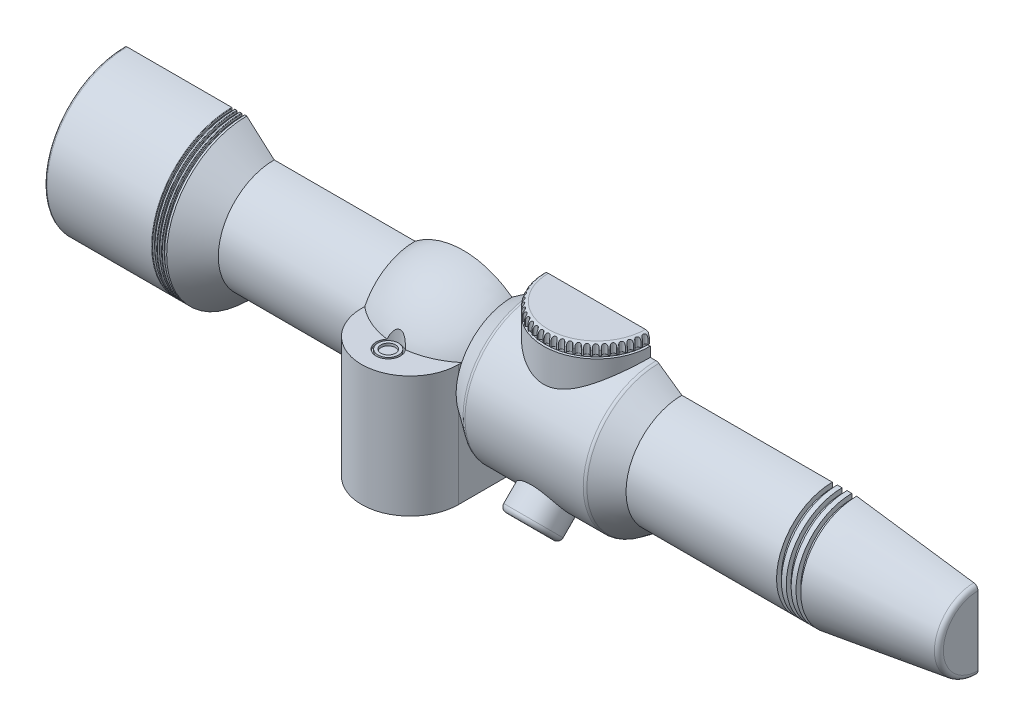
SolidWorks part; units mm, degrees
ref_plane "Front Plane" through (0, 0, 0) normal (0, 0, 1) x (1, 0, 0)
ref_plane "Top Plane" through (0, 0, 0) normal (0, 1, 0) x (1, 0, 0)
ref_plane "Right Plane" through (0, 0, 0) normal (1, 0, 0) x (0, 0, -1)
sketch "Sketch1" plane through (0, 0, 0) normal (1, 0, 0) x (0, 0, -1)
  circle A0 centre (0, 0) radius 16.5
  dimension "D1" = 33
extrude "Boss-Extrude1" add sketch "Sketch1" along normal blind 25.15
sketch "Sketch2" plane through (0, 0, 0) normal (-1, 0, 0) x (0, 0, 1)
  circle A0 centre (0, 0) radius 14.125
  dimension "D1" = 28.25
extrude "Cut-Extrude1" cut sketch "Sketch2" against normal blind 1
sketch "Sketch3" plane through (1, 0, 0) normal (-1, 0, 0) x (0, 0, 1)
  circle A0 centre (0, 0) radius 13.125
  dimension "D1" = 26.25
ref_plane "Plane1" through (25.15, 0, 0) normal (0, -1, 0) x (0, 0, 1)
extrude "Cut-Extrude6" cut sketch "Sketch3" against normal blind 1 contours A0
sketch "Sketch14" plane through (2, 0, 0) normal (-1, 0, 0) x (0, 0, 1)
  circle A0 centre (0, 0) radius 12.125
  dimension "D1" = 24.25
extrude "Cut-Extrude7" cut sketch "Sketch14" against normal blind 1
sketch "Sketch15" plane through (3, 0, 0) normal (-1, 0, 0) x (0, 0, 1)
  circle A0 centre (0, 0) radius 11.125
  dimension "D1" = 22.25
extrude "Cut-Extrude8" cut sketch "Sketch15" against normal blind 1
sketch "Sketch16" plane through (4, 0, 0) normal (-1, 0, 0) x (0, 0, 1)
  circle A0 centre (0, 0) radius 10.125
  dimension "D1" = 20.25
extrude "Cut-Extrude9" cut sketch "Sketch16" against normal blind 1
sketch "Sketch17" plane through (5, 0, 0) normal (-1, 0, 0) x (0, 0, 1)
  circle A0 centre (0, 0) radius 9.125
  dimension "D1" = 18.25
extrude "Cut-Extrude10" cut sketch "Sketch17" against normal blind 3
sketch "Sketch18" plane through (0, 0, 0) normal (0, 1, 0) x (1, 0, 0)
  line L0 (25.15, 0) -> (0, 0) construction
  line L1 (6.4671, 0) -> (8, 0)
  line L2 (8, 9.125) -> (8, -9.125) construction
  line L3 (8, 0) -> (8, 9.125)
  spline S0 degree 2 poles (8, 9.125) (6.4671, 4.5625) (6.4671, 0) knots 0 0 0 0.5 0.5 0.5
revolve "Revolve1" add sketch "Sketch18" angle 360 about axis through (25.15, 0, 0) along (-1, 0, 0)
sketch "Sketch20" plane through (0, 0, 0) normal (0, 1, 0) x (1, 0, 0)
  line L0 (25.15, 0) -> (30.8, 0)
  line L1 (25.15, -16.5) -> (25.15, 16.5) construction
  line L2 (25.15, 0) -> (0, 0) construction
  line L3 (30.8, 0) -> (30.8, 11.5)
  line L4 (30.8, 11.5) -> (25.15, 16.5)
  line L5 (25.15, 16.5) -> (25.15, 0)
  line L6 (25.15, 0) -> (25.0816, -0.0545)
  dimension "D1" = 11.5
  dimension "D2" = 5.65
revolve "Revolve5" add sketch "Sketch20" angle 360 about L0
sketch "Sketch21" plane through (30.8, 0, 0) normal (1, 0, 0) x (0, 0, -1)
  circle A0 centre (0, 0) radius 11.5
extrude "Shaft" add sketch "Sketch21" along normal blind 120
sketch "Sketch25" plane through (0, 0, 0) normal (0, 1, 0) x (1, 0, 0)
  line L0 (23.15, 16.5) -> (23.65, 16.5)
  line L1 (25.15, 16.5) -> (0, 16.5) construction
  line L2 (24.65, 16.5) -> (24.65, 16)
  line L3 (24.65, 16) -> (24.15, 16)
  line L4 (24.15, 16) -> (24.15, 16.5)
  line L5 (25.15, 16.5) -> (0, 16.5) construction
  line L7 (25.15, 16.5) -> (0, 16.5) construction
  line L8 (23.65, 16.5) -> (23.65, 16)
  line L9 (23.65, 16) -> (23.15, 16)
  line L10 (23.15, 16) -> (23.15, 16.5)
  line L11 (25.15, 16.5) -> (0, 16.5) construction
  line L12 (24.15, 16.5) -> (24.65, 16.5)
  line L13 (25.15, 16.5) -> (0, 16.5) construction
  line L14 (22.65, 16.5) -> (22.65, 16)
  line L15 (22.65, 16) -> (22.15, 16)
  line L16 (22.15, 16) -> (22.15, 16.5)
  line L17 (25.15, 16.5) -> (0, 16.5) construction
  line L18 (22.15, 16.5) -> (22.65, 16.5)
  line L20 (23.65, 16.5) -> (23.6371, 16.4877)
  dimension "D1" = 0.5
  dimension "D2" = 0.5
  dimension "D3" = 0.5
  dimension "D4" = 0.5
  dimension "D5" = 0.5
  dimension "D6" = 0.5
  dimension "D8" = 0.5
  dimension "D9" = 0.5
revolve "Cut-Revolve13" cut sketch "Sketch25" angle 360 about axis through (25.15, 0, 0) along (-1, 0, 0)
fillet "Fillet1" radius 0.1 6 edges at (24.65, 0, -16.5) (24.15, 0, -16.5) (23.65, 0, -16.5) (23.15, 0, -16.5) (22.65, 0, -16.5) (22.15, 0, -16.5)
fillet "Fillet2" radius 0.5 1 edges at (0, 0, -16.5)
sketch "Sketch26" plane through (0, 0, 0) normal (0, 1, 0) x (1, 0, 0)
  line L0 (150.8, -11.5) -> (150.8, 0)
  line L1 (150.8, -11.5) -> (150.8, 11.5) construction
  line L2 (150.8, 0) -> (175.8, 0)
  line L3 (150.8, 0) -> (30.8, 0) construction
  line L4 (175.8, 0) -> (175.8, -7.1302)
  line L5 (174.9386, -8.1206) -> (150.8, -11.5)
  arc A0 (175.8, -7.1302) -> (174.9386, -8.1206) centre (174.8, -7.1302) cw
  point P12 (175.8, -8)
  dimension "D3" = 1
  dimension "D1" = 25
  dimension "D2" = 8
revolve "Revolve6" add sketch "Sketch26" angle 360 about axis through (150.8, 0, 0) along (-1, 0, 0)
sketch "Sketch27" plane through (0, 0, 0) normal (0, 1, 0) x (1, 0, 0)
  line L0 (147.8, -11.5) -> (147.8, -10.5)
  line L1 (150.8, -11.5) -> (149.8, -11.5)
  line L2 (150.8, -11.5) -> (150.8, -10.5)
  line L3 (150.8, -10.5) -> (149.8, -10.5)
  line L4 (149.8, -11.5) -> (149.8, -10.5)
  line L5 (148.8, -11.5) -> (147.8, -11.5)
  line L6 (148.8, -11.5) -> (148.8, -10.5)
  line L7 (148.8, -10.5) -> (147.8, -10.5)
  line L8 (145.8, -11.5) -> (145.8, -10.5)
  line L9 (146.8, -11.5) -> (145.8, -11.5)
  line L10 (146.8, -11.5) -> (146.8, -10.5)
  line L11 (146.8, -10.5) -> (145.8, -10.5)
  dimension "D1" = 1
  dimension "D2" = 1
  dimension "D3" = 3
revolve "Cut-Revolve14" cut sketch "Sketch27" angle 360 about axis through (150.8, 0, 0) along (-1, 0, 0)
sketch "Sketch28" plane through (0, 0, 0) normal (0, 1, 0) x (1, 0, 0)
  line L0 (145.8, 0) -> (30.8, 0) construction
  line L1 (59.8, 11) -> (59.8, -11)
  line L2 (79.8, -11) -> (79.8, 11)
  line L3 (30.8, 11.5) -> (30.8, -11.5) construction
  arc A0 (79.8, 11) -> (59.8, 11) centre (69.8, 11) ccw
  arc A1 (59.8, -11) -> (79.8, -11) centre (69.8, -11) ccw
  dimension "D1" = 20
  dimension "D2" = 20
  dimension "D3" = 22
  dimension "D4" = 11
  dimension "D5" = 29
extrude "Boss-Extrude2" add sketch "Sketch28" against normal blind 20 and the other way blind 5
sketch "Sketch29" plane through (0, -20, 0) normal (0, -1, 0) x (1, 0, 0)
  circle A0 centre (69.8, -11) radius 2.75
  circle A1 centre (69.8, 7) radius 2.75
  dimension "D1" = 5.5
  dimension "D3" = 5.5
  dimension "D2" = 18
extrude "Cut-Extrude11" cut sketch "Sketch29" against normal blind 10
sketch "Sketch30" plane through (0, 0, 0) normal (0, 1, 0) x (1, 0, 0)
  line L0 (69.8, 14.8562) -> (54.6498, 14.8562) construction
  line L2 (59.8125, 11.5) -> (79.7875, 11.5)
  arc A0 (59.8125, 11.5) -> (79.7875, 11.5) centre (69.8, -1.6827) cw
revolve "Revolve7" add sketch "Sketch30" angle 180 about axis through (150.8, 0, 0) along (-1, 0, 0)
sketch "Sketch31" plane through (0, 5, 0) normal (0, 1, 0) x (1, 0, 0)
  circle A0 centre (69.8, 15.5) radius 2.5
  arc A1 (79.8, 11) -> (59.8, 11) centre (69.8, 11) ccw construction
  point P2 (69.8, 21)
  dimension "D1" = 5
  dimension "D2" = 5.5
extrude "Cut-Extrude12" cut sketch "Sketch31" against normal blind 0.5 and the other way blind 10
sketch "Sketch32" plane through (0, 4.5, 0) normal (0, 1, 0) x (1, 0, 0)
  circle A0 centre (69.8, 15.5) radius 2.125
  circle A1 centre (69.8, 15.5) radius 1.5
  dimension "D1" = 4.25
  dimension "D2" = 3
extrude "Boss-Extrude3" add sketch "Sketch32" along normal blind 0.5
mirror "Mirror2" about plane through (0, 0, 0) normal (0, 0, 1) of "Boss-Extrude3", "Cut-Extrude12"
sketch "Sketch33" plane through (0, 0, 0) normal (0, 1, 0) x (1, 0, 0)
  line L0 (79.7875, 11.5) -> (84.5293, 14.8192)
  line L1 (85.1027, 15) -> (109.4723, 15)
  line L2 (110.0457, 14.8192) -> (114.7875, 11.5)
  line L3 (145.8, 11.5) -> (79.7875, 11.5) construction
  line L4 (114.7875, 11.5) -> (79.7875, 11.5)
  line L5 (145.8, 0) -> (79.7875, 0) construction
  arc A0 (110.0457, 14.8192) -> (109.4723, 15) centre (109.4723, 14) ccw
  arc A1 (85.1027, 15) -> (84.5293, 14.8192) centre (85.1027, 14) ccw
  point P11 (109.7875, 15)
  point P14 (84.7875, 15)
  dimension "D5" = 1
  dimension "D1" = 5
  dimension "D2" = 5
  dimension "D3" = 25
  dimension "D4" = 15
revolve "Revolve8" add sketch "Sketch33" angle 360 about axis through (150.8, 0, 0) along (-1, 0, 0)
sketch "Sketch34" plane through (0, 0, 0) normal (0, 0, 1) x (1, 0, 0)
  line L0 (85.1027, 0) -> (109.4723, 0) construction
  line L1 (114.7875, 11.5) -> (114.7875, -11.5) construction
  circle A0 centre (97.2875, 0) radius 12
  dimension "D2" = 24
  dimension "D1" = 17.5
extrude "Boss-Extrude4" add sketch "Sketch34" against normal blind 19.5
fillet "Fillet3" radius 1 1 edges at (109.2875, 0, -19.5)
sketch "Sketch36" plane through (0, 0, 0) normal (0, 1, 0) x (1, 0, 0)
  line L1 (85.2875, 18.5) -> (85.2875, 15) construction
  line L2 (85.2875, 17.5) -> (85.7875, 17.5)
  line L3 (85.2875, 17.5) -> (85.2875, 17)
  line L4 (85.2875, 17) -> (85.7875, 17)
  line L6 (85.7875, 17.5) -> (85.7875, 17)
  line L7 (109.2875, 18.5) -> (85.2875, 18.5) construction
  dimension "D1" = 0.5
  dimension "D2" = 0.5
  dimension "D3" = 1
revolve "Cut-Revolve15" cut sketch "Sketch36" angle 360 about axis through (97.2875, 0, -19.5) along (0, 0, 1)
sketch "Sketch38" plane through (0, 0, -19.5) normal (0, 0, -1) x (-1, 0, 0)
  line L0 (-97.2875, 0) -> (-97.2875, 15.7443) construction
sketch "Sketch39" plane through (0, 0, -19.5) normal (0, 0, -1) x (-1, 0, 0)
  line L0 (-97.2875, 0) -> (-97.2875, 15.7443) construction
  circle A0 centre (-97.2875, 12) radius 0.5
  circle A1 centre (-97.2875, 0) radius 12 construction
  dimension "D1" = 1
extrude "Cut-Extrude13" cut sketch "Sketch39" against normal up to next
pattern_circular "CirPattern1" count 53 over 360 about axis through (97.2875, 0, 0) along (0, 0, 1) of "Cut-Extrude13"
sketch "Sketch40" plane through (0, 0, 0) normal (0, 1, 0) x (1, 0, 0)
  line L0 (85.1027, 0) -> (109.4723, 0) construction
  line L1 (97.2875, 17) -> (97.2875, 14.9999) construction
  circle A0 centre (97.2875, 0) radius 11
  dimension "D1" = 22
extrude "Boss-Extrude5" add sketch "Sketch40" along normal blind 19.5
ref_plane "Plane3" through (0, 0, 0) normal (0, 0.7071, -0.7071) x (-1, 0, 0)
sketch "Sketch41" plane through (0, 0, 0) normal (0, 0.7071, -0.7071) x (-1, 0, 0)
  line L0 (-85.1027, 0) -> (-109.4723, 0) construction
  circle A0 centre (-97.2875, 0) radius 5
  dimension "D1" = 10
extrude "Boss-Extrude6" add sketch "Sketch41" against normal blind 19.5
fillet "Fillet4" radius 1 1 edges at (97.2875, -10.253, 17.3241)
sketch "Sketch43" plane through (0, 0, 0) normal (0, 0, 1) x (1, 0, 0)
  line L0 (108.2875, 15) -> (108.2875, 19.5) construction
  line L1 (108.2875, 17.5) -> (107.7875, 17.5)
  line L2 (108.2875, 17.5) -> (108.2875, 17)
  line L3 (108.2875, 17) -> (107.7875, 17)
  line L4 (107.7875, 17.5) -> (107.7875, 17)
  line L5 (108.2875, 19.5) -> (86.2875, 19.5) construction
  dimension "D1" = 0.5
  dimension "D2" = 0.5
  dimension "D3" = 2
revolve "Cut-Revolve16" cut sketch "Sketch43" angle 360 about axis through (97.2875, 19.5, 0) along (0, -1, 0)
fillet "Fillet5" radius 1 1 edges at (97.2875, 19.5, 11)
sketch "Sketch44" plane through (0, 19.5, 0) normal (0, 1, 0) x (1, 0, 0)
  circle A0 centre (97.2875, 11) radius 0.5
  arc A1 (101.7596, 10.0499) -> (92.8154, 10.0499) centre (97.2875, 0) ccw construction
  dimension "D1" = 1
extrude "Cut-Extrude14" cut sketch "Sketch44" against normal up to next
pattern_circular "CirPattern2" count 53 over 360 about axis through (97.2875, 0, 0) along (0, 1, 0) of "Cut-Extrude14"
sketch "Sketch45" plane through (0, 0, 0) normal (0, 0, 1) x (1, 0, 0)
  line L1 (-11.3661, 27.4524) -> (188.3957, 27.4524)
  line L2 (-11.3661, 27.4524) -> (-11.3661, -27.3687)
  line L3 (-11.3661, -27.3687) -> (188.3957, -27.3687)
  line L4 (188.3957, 27.4524) -> (188.3957, -27.3687)
extrude "Cut-Extrude15" cut sketch "Sketch45" against normal through all
sketch "Sketch46" plane through (0, 0, 0) normal (0, 0, -1) x (-1, 0, 0)
  line L0 (-150.8, 0) -> (-174.9386, 0) construction
  line L1 (-22.05, 0) -> (-0.5, 0) construction
  line L2 (-59.8125, 0) -> (-30.8, 0) construction
  line L3 (-84.5293, 0) -> (-79.7875, 0) construction
  line L4 (-69.8, 5) -> (-69.8, -20) construction
  line L5 (-175.8, -7.1302) -> (-175.8, 7.1302) construction
  circle A0 centre (-155.8, 0) radius 2.75
  circle A1 centre (-16.4671, 0) radius 2.75
  circle A2 centre (-69.8, 0) radius 2.75
  dimension "D1" = 5.5
  dimension "D2" = 5.5
  dimension "D4" = 5.5
  dimension "D3" = 10
  dimension "D5" = 20
extrude "Cut-Extrude16" cut sketch "Sketch46" against normal blind 5
